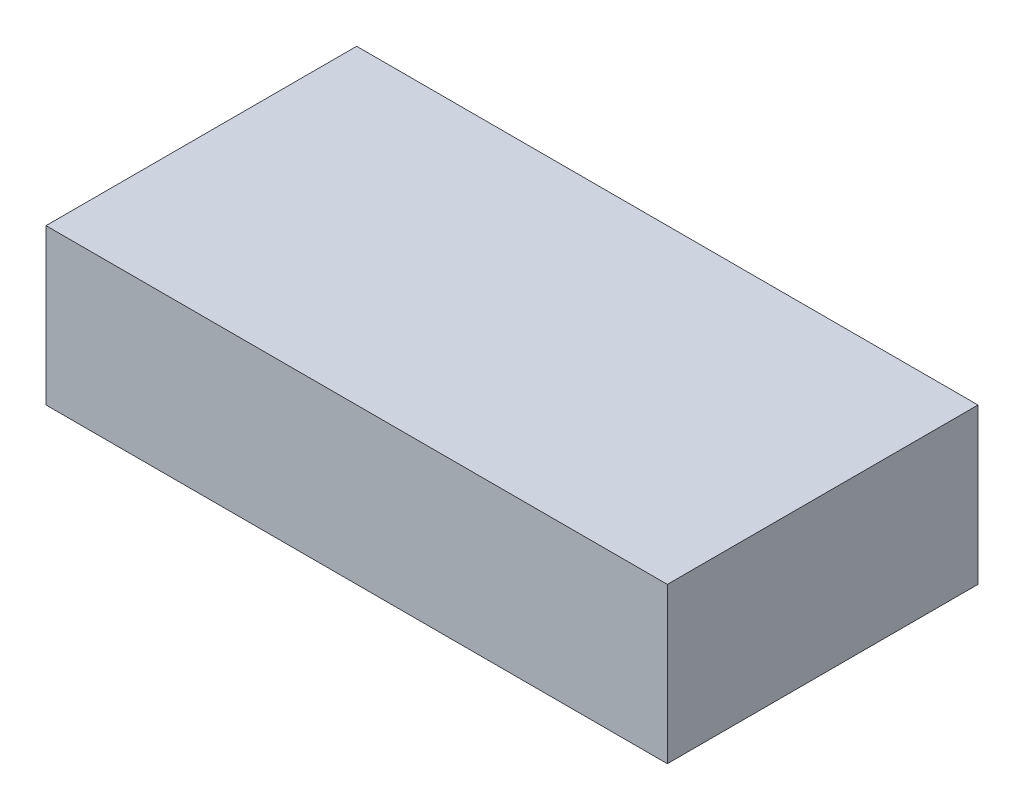
SolidWorks part; units mm, degrees
ref_plane "Front Plane" through (0, 0, 0) normal (0, 0, 1) x (1, 0, 0)
ref_plane "Top Plane" through (0, 0, 0) normal (0, 1, 0) x (1, 0, 0)
ref_plane "Right Plane" through (0, 0, 0) normal (1, 0, 0) x (0, 0, -1)
other "Configuration Table"
sketch "Sketch1" plane through (0, 0, 0) normal (0, 0, 1) x (1, 0, 0)
  line L1 (1218, 1628) -> (1298, 1628)
  line L2 (1218, 1628) -> (1218, 1648)
  line L3 (1218, 1648) -> (1298, 1648)
  line L4 (1298, 1628) -> (1298, 1648)
extrude "DET2_klemens_kutusu_dilimi_1" add sketch "Sketch1" against normal blind 40 from offset 760 separate body
